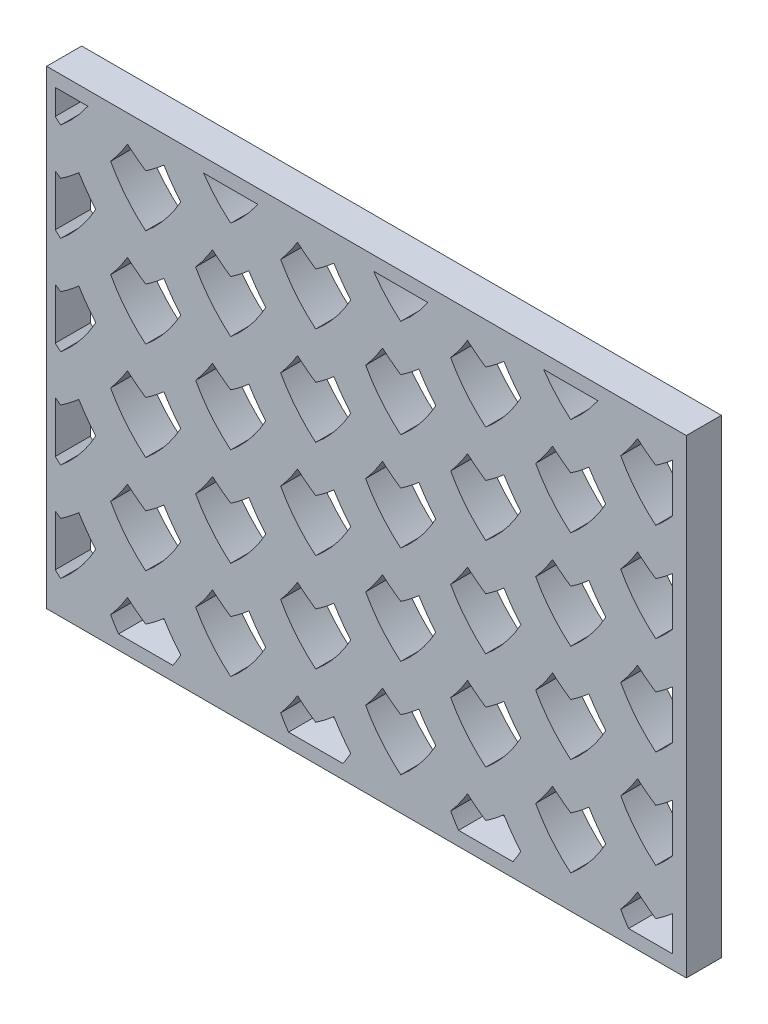
SolidWorks part; units mm, degrees
ref_plane "Front Plane" through (0, 0, 0) normal (0, 0, 1) x (1, 0, 0)
ref_plane "Top Plane" through (0, 0, 0) normal (0, 1, 0) x (1, 0, 0)
ref_plane "Right Plane" through (0, 0, 0) normal (1, 0, 0) x (0, 0, -1)
sketch "Sketch1" plane through (0, 0, 0) normal (0, 0, 1) x (1, 0, 0)
  line L0 (-49.5912, -69.1179) -> (-37.4668, -62.1179) construction
  arc A0 (-49.5912, -69.1179) -> (-54.5912, -63.0266) centre (-35.8066, -52.7051) cw
  arc A1 (-54.5912, -63.0266) -> (-52.1853, -59.6939) centre (-73.3707, -46.9345) ccw
  arc A2 (-49.5912, -61.697) -> (-52.1853, -59.6939) centre (-35.8066, -41.1639) cw
  arc A3 (-49.5912, -61.697) -> (-46.9971, -59.6939) centre (-63.3758, -41.1639) ccw
  arc A4 (-44.5911, -63.0266) -> (-46.9971, -59.6939) centre (-25.8117, -46.9345) cw
  arc A5 (-49.5912, -69.1179) -> (-44.5911, -63.0266) centre (-63.3758, -52.7051) ccw
  arc A6 (-37.4668, -62.1179) -> (-42.4669, -56.0266) centre (-23.6822, -45.7051) cw
  arc A7 (-42.4669, -56.0266) -> (-40.061, -52.6939) centre (-61.2463, -39.9345) ccw
  arc A8 (-37.4668, -54.697) -> (-40.061, -52.6939) centre (-23.6822, -34.1639) cw
  arc A9 (-37.4668, -54.697) -> (-34.8727, -52.6939) centre (-51.2514, -34.1639) ccw
  arc A10 (-32.4668, -56.0266) -> (-34.8727, -52.6939) centre (-13.6873, -39.9345) cw
  arc A11 (-37.4668, -62.1179) -> (-32.4668, -56.0266) centre (-51.2514, -45.7051) ccw
  arc A12 (-25.3425, -55.1179) -> (-30.3425, -49.0266) centre (-11.5579, -38.7051) cw
  arc A13 (-30.3425, -49.0266) -> (-27.9366, -45.6939) centre (-49.122, -32.9345) ccw
  arc A14 (-25.3425, -47.697) -> (-27.9366, -45.6939) centre (-11.5579, -27.1639) cw
  arc A15 (-25.3425, -47.697) -> (-22.7483, -45.6939) centre (-39.1271, -27.1639) ccw
  arc A16 (-20.3424, -49.0266) -> (-22.7483, -45.6939) centre (-1.563, -32.9345) cw
  arc A17 (-25.3425, -55.1179) -> (-20.3424, -49.0266) centre (-39.1271, -38.7051) ccw
  arc A18 (-13.2181, -48.1179) -> (-18.2182, -42.0266) centre (0.5665, -31.7051) cw
  arc A19 (-18.2182, -42.0266) -> (-15.8123, -38.6939) centre (-36.9976, -25.9345) ccw
  arc A20 (-13.2181, -40.697) -> (-15.8123, -38.6939) centre (0.5665, -20.1639) cw
  arc A21 (-13.2181, -40.697) -> (-10.624, -38.6939) centre (-27.0027, -20.1639) ccw
  arc A22 (-8.2181, -42.0266) -> (-10.624, -38.6939) centre (10.5614, -25.9345) cw
  arc A23 (-13.2181, -48.1179) -> (-8.2181, -42.0266) centre (-27.0027, -31.7051) ccw
  arc A24 (-1.0938, -41.1179) -> (-6.0938, -35.0266) centre (12.6908, -24.7051) cw
  arc A25 (-6.0938, -35.0266) -> (-3.6879, -31.6939) centre (-24.8733, -18.9345) ccw
  arc A26 (-1.0938, -33.697) -> (-3.6879, -31.6939) centre (12.6908, -13.1639) cw
  arc A27 (-1.0938, -33.697) -> (1.5004, -31.6939) centre (-14.8783, -13.1639) ccw
  arc A28 (3.9063, -35.0266) -> (1.5004, -31.6939) centre (22.6857, -18.9345) cw
  arc A29 (-1.0938, -41.1179) -> (3.9063, -35.0266) centre (-14.8783, -24.7051) ccw
  arc A30 (11.0306, -34.1179) -> (6.0305, -28.0266) centre (24.8152, -17.7051) cw
  arc A31 (6.0305, -28.0266) -> (8.4365, -24.6939) centre (-12.7489, -11.9345) ccw
  arc A32 (11.0306, -26.697) -> (8.4365, -24.6939) centre (24.8152, -6.1639) cw
  arc A33 (11.0306, -26.697) -> (13.6247, -24.6939) centre (-2.754, -6.1639) ccw
  arc A34 (16.0306, -28.0266) -> (13.6247, -24.6939) centre (34.8101, -11.9345) cw
  arc A35 (11.0306, -34.1179) -> (16.0306, -28.0266) centre (-2.754, -17.7051) ccw
  arc A36 (23.1549, -27.1179) -> (18.1549, -21.0266) centre (36.9395, -10.7051) cw
  arc A37 (18.1549, -21.0266) -> (20.5608, -17.6939) centre (-0.6246, -4.9345) ccw
  arc A38 (23.1549, -19.697) -> (20.5608, -17.6939) centre (36.9395, 0.8361) cw
  arc A39 (23.1549, -19.697) -> (25.7491, -17.6939) centre (9.3704, 0.8361) ccw
  arc A40 (28.155, -21.0266) -> (25.7491, -17.6939) centre (46.9344, -4.9345) cw
  arc A41 (23.1549, -27.1179) -> (28.155, -21.0266) centre (9.3704, -10.7051) ccw
  arc A42 (35.2793, -20.1179) -> (30.2792, -14.0266) centre (49.0639, -3.7051) cw
  arc A43 (30.2792, -14.0266) -> (32.6852, -10.6939) centre (11.4998, 2.0655) ccw
  arc A44 (35.2793, -12.697) -> (32.6852, -10.6939) centre (49.0639, 7.8361) cw
  arc A45 (35.2793, -12.697) -> (37.8734, -10.6939) centre (21.4947, 7.8361) ccw
  arc A46 (40.2794, -14.0266) -> (37.8734, -10.6939) centre (59.0588, 2.0655) cw
  arc A47 (35.2793, -20.1179) -> (40.2794, -14.0266) centre (21.4947, -3.7051) ccw
  arc A48 (47.4037, -13.1179) -> (42.4036, -7.0266) centre (61.1882, 3.2949) cw
  arc A49 (42.4036, -7.0266) -> (44.8095, -3.6939) centre (23.6242, 9.0655) ccw
  arc A50 (47.4037, -5.697) -> (44.8095, -3.6939) centre (61.1882, 14.8361) cw
  arc A51 (47.4037, -5.697) -> (49.9978, -3.6939) centre (33.6191, 14.8361) ccw
  arc A52 (52.4037, -7.0266) -> (49.9978, -3.6939) centre (71.1832, 9.0655) cw
  arc A53 (47.4037, -13.1179) -> (52.4037, -7.0266) centre (33.6191, 3.2949) ccw
  arc A54 (59.528, -6.1179) -> (54.528, -0.0266) centre (73.3126, 10.2949) cw
  arc A55 (54.528, -0.0266) -> (56.9339, 3.3061) centre (35.7485, 16.0655) ccw
  arc A56 (59.528, 1.303) -> (56.9339, 3.3061) centre (73.3126, 21.8361) cw
  arc A57 (59.528, 1.303) -> (62.1221, 3.3061) centre (45.7434, 21.8361) ccw
  arc A58 (64.5281, -0.0266) -> (62.1221, 3.3061) centre (83.3075, 16.0655) cw
  arc A59 (59.528, -6.1179) -> (64.5281, -0.0266) centre (45.7434, 10.2949) ccw
  arc A60 (-37.4668, -48.1179) -> (-42.4669, -42.0266) centre (-23.6822, -31.7051) cw
  arc A61 (-42.4669, -42.0266) -> (-40.061, -38.6939) centre (-61.2463, -25.9345) ccw
  arc A62 (-37.4668, -40.697) -> (-40.061, -38.6939) centre (-23.6822, -20.1639) cw
  arc A63 (-37.4668, -40.697) -> (-34.8727, -38.6939) centre (-51.2514, -20.1639) ccw
  arc A64 (-32.4668, -42.0266) -> (-34.8727, -38.6939) centre (-13.6873, -25.9345) cw
  arc A65 (-37.4668, -48.1179) -> (-32.4668, -42.0266) centre (-51.2514, -31.7051) ccw
  arc A66 (-25.3425, -41.1179) -> (-30.3425, -35.0266) centre (-11.5579, -24.7051) cw
  arc A67 (-30.3425, -35.0266) -> (-27.9366, -31.6939) centre (-49.122, -18.9345) ccw
  arc A68 (-25.3425, -33.697) -> (-27.9366, -31.6939) centre (-11.5579, -13.1639) cw
  arc A69 (-25.3425, -33.697) -> (-22.7483, -31.6939) centre (-39.1271, -13.1639) ccw
  arc A70 (-20.3424, -35.0266) -> (-22.7483, -31.6939) centre (-1.563, -18.9345) cw
  arc A71 (-25.3425, -41.1179) -> (-20.3424, -35.0266) centre (-39.1271, -24.7051) ccw
  arc A72 (-13.2181, -34.1179) -> (-18.2182, -28.0266) centre (0.5665, -17.7051) cw
  arc A73 (-18.2182, -28.0266) -> (-15.8123, -24.6939) centre (-36.9976, -11.9345) ccw
  arc A74 (-13.2181, -26.697) -> (-15.8123, -24.6939) centre (0.5665, -6.1639) cw
  arc A75 (-13.2181, -26.697) -> (-10.624, -24.6939) centre (-27.0027, -6.1639) ccw
  arc A76 (-8.2181, -28.0266) -> (-10.624, -24.6939) centre (10.5614, -11.9345) cw
  arc A77 (-13.2181, -34.1179) -> (-8.2181, -28.0266) centre (-27.0027, -17.7051) ccw
  arc A78 (-1.0938, -27.1179) -> (-6.0938, -21.0266) centre (12.6908, -10.7051) cw
  arc A79 (-6.0938, -21.0266) -> (-3.6879, -17.6939) centre (-24.8733, -4.9345) ccw
  arc A80 (-1.0938, -19.697) -> (-3.6879, -17.6939) centre (12.6908, 0.8361) cw
  arc A81 (-1.0938, -19.697) -> (1.5004, -17.6939) centre (-14.8783, 0.8361) ccw
  arc A82 (3.9063, -21.0266) -> (1.5004, -17.6939) centre (22.6857, -4.9345) cw
  arc A83 (-1.0938, -27.1179) -> (3.9063, -21.0266) centre (-14.8783, -10.7051) ccw
  arc A84 (11.0306, -20.1179) -> (6.0305, -14.0266) centre (24.8152, -3.7051) cw
  arc A85 (6.0305, -14.0266) -> (8.4365, -10.6939) centre (-12.7489, 2.0655) ccw
  arc A86 (11.0306, -12.697) -> (8.4365, -10.6939) centre (24.8152, 7.8361) cw
  arc A87 (11.0306, -12.697) -> (13.6247, -10.6939) centre (-2.754, 7.8361) ccw
  arc A88 (16.0306, -14.0266) -> (13.6247, -10.6939) centre (34.8101, 2.0655) cw
  arc A89 (11.0306, -20.1179) -> (16.0306, -14.0266) centre (-2.754, -3.7051) ccw
  arc A90 (23.1549, -13.1179) -> (18.1549, -7.0266) centre (36.9395, 3.2949) cw
  arc A91 (18.1549, -7.0266) -> (20.5608, -3.6939) centre (-0.6246, 9.0655) ccw
  arc A92 (23.1549, -5.697) -> (20.5608, -3.6939) centre (36.9395, 14.8361) cw
  arc A93 (23.1549, -5.697) -> (25.7491, -3.6939) centre (9.3704, 14.8361) ccw
  arc A94 (28.155, -7.0266) -> (25.7491, -3.6939) centre (46.9344, 9.0655) cw
  arc A95 (23.1549, -13.1179) -> (28.155, -7.0266) centre (9.3704, 3.2949) ccw
  arc A96 (35.2793, -6.1179) -> (30.2792, -0.0266) centre (49.0639, 10.2949) cw
  arc A97 (30.2792, -0.0266) -> (32.6852, 3.3061) centre (11.4998, 16.0655) ccw
  arc A98 (35.2793, 1.303) -> (32.6852, 3.3061) centre (49.0639, 21.8361) cw
  arc A99 (35.2793, 1.303) -> (37.8734, 3.3061) centre (21.4947, 21.8361) ccw
  arc A100 (40.2794, -0.0266) -> (37.8734, 3.3061) centre (59.0588, 16.0655) cw
  arc A101 (35.2793, -6.1179) -> (40.2794, -0.0266) centre (21.4947, 10.2949) ccw
  arc A102 (47.4037, 0.8821) -> (42.4036, 6.9734) centre (61.1882, 17.2949) cw
  arc A103 (42.4036, 6.9734) -> (44.8095, 10.3061) centre (23.6242, 23.0655) ccw
  arc A104 (47.4037, 8.303) -> (44.8095, 10.3061) centre (61.1882, 28.8361) cw
  arc A105 (47.4037, 8.303) -> (49.9978, 10.3061) centre (33.6191, 28.8361) ccw
  arc A106 (52.4037, 6.9734) -> (49.9978, 10.3061) centre (71.1832, 23.0655) cw
  arc A107 (47.4037, 0.8821) -> (52.4037, 6.9734) centre (33.6191, 17.2949) ccw
  arc A108 (59.528, 7.8821) -> (54.528, 13.9734) centre (73.3126, 24.2949) cw
  arc A109 (54.528, 13.9734) -> (56.9339, 17.3061) centre (35.7485, 30.0655) ccw
  arc A110 (59.528, 15.303) -> (56.9339, 17.3061) centre (73.3126, 35.8361) cw
  arc A111 (59.528, 15.303) -> (62.1221, 17.3061) centre (45.7434, 35.8361) ccw
  arc A112 (64.5281, 13.9734) -> (62.1221, 17.3061) centre (83.3075, 30.0655) cw
  arc A113 (59.528, 7.8821) -> (64.5281, 13.9734) centre (45.7434, 24.2949) ccw
  arc A114 (-37.4668, -34.1179) -> (-42.4669, -28.0266) centre (-23.6822, -17.7051) cw
  arc A115 (-42.4669, -28.0266) -> (-40.061, -24.6939) centre (-61.2463, -11.9345) ccw
  arc A116 (-37.4668, -26.697) -> (-40.061, -24.6939) centre (-23.6822, -6.1639) cw
  arc A117 (-37.4668, -26.697) -> (-34.8727, -24.6939) centre (-51.2514, -6.1639) ccw
  arc A118 (-32.4668, -28.0266) -> (-34.8727, -24.6939) centre (-13.6873, -11.9345) cw
  arc A119 (-37.4668, -34.1179) -> (-32.4668, -28.0266) centre (-51.2514, -17.7051) ccw
  arc A120 (-25.3425, -27.1179) -> (-30.3425, -21.0266) centre (-11.5579, -10.7051) cw
  arc A121 (-30.3425, -21.0266) -> (-27.9366, -17.6939) centre (-49.122, -4.9345) ccw
  arc A122 (-25.3425, -19.697) -> (-27.9366, -17.6939) centre (-11.5579, 0.8361) cw
  arc A123 (-25.3425, -19.697) -> (-22.7483, -17.6939) centre (-39.1271, 0.8361) ccw
  arc A124 (-20.3424, -21.0266) -> (-22.7483, -17.6939) centre (-1.563, -4.9345) cw
  arc A125 (-25.3425, -27.1179) -> (-20.3424, -21.0266) centre (-39.1271, -10.7051) ccw
  arc A126 (-13.2181, -20.1179) -> (-18.2182, -14.0266) centre (0.5665, -3.7051) cw
  arc A127 (-18.2182, -14.0266) -> (-15.8123, -10.6939) centre (-36.9976, 2.0655) ccw
  arc A128 (-13.2181, -12.697) -> (-15.8123, -10.6939) centre (0.5665, 7.8361) cw
  arc A129 (-13.2181, -12.697) -> (-10.624, -10.6939) centre (-27.0027, 7.8361) ccw
  arc A130 (-8.2181, -14.0266) -> (-10.624, -10.6939) centre (10.5614, 2.0655) cw
  arc A131 (-13.2181, -20.1179) -> (-8.2181, -14.0266) centre (-27.0027, -3.7051) ccw
  arc A132 (-1.0938, -13.1179) -> (-6.0938, -7.0266) centre (12.6908, 3.2949) cw
  arc A133 (-6.0938, -7.0266) -> (-3.6879, -3.6939) centre (-24.8733, 9.0655) ccw
  arc A134 (-1.0938, -5.697) -> (-3.6879, -3.6939) centre (12.6908, 14.8361) cw
  arc A135 (-1.0938, -5.697) -> (1.5004, -3.6939) centre (-14.8783, 14.8361) ccw
  arc A136 (3.9063, -7.0266) -> (1.5004, -3.6939) centre (22.6857, 9.0655) cw
  arc A137 (-1.0938, -13.1179) -> (3.9063, -7.0266) centre (-14.8783, 3.2949) ccw
  arc A138 (11.0306, -6.1179) -> (6.0305, -0.0266) centre (24.8152, 10.2949) cw
  arc A139 (6.0305, -0.0266) -> (8.4365, 3.3061) centre (-12.7489, 16.0655) ccw
  arc A140 (11.0306, 1.303) -> (8.4365, 3.3061) centre (24.8152, 21.8361) cw
  arc A141 (11.0306, 1.303) -> (13.6247, 3.3061) centre (-2.754, 21.8361) ccw
  arc A142 (16.0306, -0.0266) -> (13.6247, 3.3061) centre (34.8101, 16.0655) cw
  arc A143 (11.0306, -6.1179) -> (16.0306, -0.0266) centre (-2.754, 10.2949) ccw
  arc A144 (23.1549, 0.8821) -> (18.1549, 6.9734) centre (36.9395, 17.2949) cw
  arc A145 (18.1549, 6.9734) -> (20.5608, 10.3061) centre (-0.6246, 23.0655) ccw
  arc A146 (23.1549, 8.303) -> (20.5608, 10.3061) centre (36.9395, 28.8361) cw
  arc A147 (23.1549, 8.303) -> (25.7491, 10.3061) centre (9.3704, 28.8361) ccw
  arc A148 (28.155, 6.9734) -> (25.7491, 10.3061) centre (46.9344, 23.0655) cw
  arc A149 (23.1549, 0.8821) -> (28.155, 6.9734) centre (9.3704, 17.2949) ccw
  arc A150 (35.2793, 7.8821) -> (30.2792, 13.9734) centre (49.0639, 24.2949) cw
  arc A151 (30.2792, 13.9734) -> (32.6852, 17.3061) centre (11.4998, 30.0655) ccw
  arc A152 (35.2793, 15.303) -> (32.6852, 17.3061) centre (49.0639, 35.8361) cw
  arc A153 (35.2793, 15.303) -> (37.8734, 17.3061) centre (21.4947, 35.8361) ccw
  arc A154 (40.2794, 13.9734) -> (37.8734, 17.3061) centre (59.0588, 30.0655) cw
  arc A155 (35.2793, 7.8821) -> (40.2794, 13.9734) centre (21.4947, 24.2949) ccw
  arc A156 (47.4037, 14.8821) -> (42.4036, 20.9734) centre (61.1882, 31.2949) cw
  arc A157 (42.4036, 20.9734) -> (44.8095, 24.3061) centre (23.6242, 37.0655) ccw
  arc A158 (47.4037, 22.303) -> (44.8095, 24.3061) centre (61.1882, 42.8361) cw
  arc A159 (47.4037, 22.303) -> (49.9978, 24.3061) centre (33.6191, 42.8361) ccw
  arc A160 (52.4037, 20.9734) -> (49.9978, 24.3061) centre (71.1832, 37.0655) cw
  arc A161 (47.4037, 14.8821) -> (52.4037, 20.9734) centre (33.6191, 31.2949) ccw
  arc A162 (59.528, 21.8821) -> (54.528, 27.9734) centre (73.3126, 38.2949) cw
  arc A163 (54.528, 27.9734) -> (56.9339, 31.3061) centre (35.7485, 44.0655) ccw
  arc A164 (59.528, 29.303) -> (56.9339, 31.3061) centre (73.3126, 49.8361) cw
  arc A165 (59.528, 29.303) -> (62.1221, 31.3061) centre (45.7434, 49.8361) ccw
  arc A166 (64.5281, 27.9734) -> (62.1221, 31.3061) centre (83.3075, 44.0655) cw
  arc A167 (59.528, 21.8821) -> (64.5281, 27.9734) centre (45.7434, 38.2949) ccw
  arc A168 (-37.4668, -20.1179) -> (-42.4669, -14.0266) centre (-23.6822, -3.7051) cw
  arc A169 (-42.4669, -14.0266) -> (-40.061, -10.6939) centre (-61.2463, 2.0655) ccw
  arc A170 (-37.4668, -12.697) -> (-40.061, -10.6939) centre (-23.6822, 7.8361) cw
  arc A171 (-37.4668, -12.697) -> (-34.8727, -10.6939) centre (-51.2514, 7.8361) ccw
  arc A172 (-32.4668, -14.0266) -> (-34.8727, -10.6939) centre (-13.6873, 2.0655) cw
  arc A173 (-37.4668, -20.1179) -> (-32.4668, -14.0266) centre (-51.2514, -3.7051) ccw
  arc A174 (-25.3425, -13.1179) -> (-30.3425, -7.0266) centre (-11.5579, 3.2949) cw
  arc A175 (-30.3425, -7.0266) -> (-27.9366, -3.6939) centre (-49.122, 9.0655) ccw
  arc A176 (-25.3425, -5.697) -> (-27.9366, -3.6939) centre (-11.5579, 14.8361) cw
  arc A177 (-25.3425, -5.697) -> (-22.7483, -3.6939) centre (-39.1271, 14.8361) ccw
  arc A178 (-20.3424, -7.0266) -> (-22.7483, -3.6939) centre (-1.563, 9.0655) cw
  arc A179 (-25.3425, -13.1179) -> (-20.3424, -7.0266) centre (-39.1271, 3.2949) ccw
  arc A180 (-13.2181, -6.1179) -> (-18.2182, -0.0266) centre (0.5665, 10.2949) cw
  arc A181 (-18.2182, -0.0266) -> (-15.8123, 3.3061) centre (-36.9976, 16.0655) ccw
  arc A182 (-13.2181, 1.303) -> (-15.8123, 3.3061) centre (0.5665, 21.8361) cw
  arc A183 (-13.2181, 1.303) -> (-10.624, 3.3061) centre (-27.0027, 21.8361) ccw
  arc A184 (-8.2181, -0.0266) -> (-10.624, 3.3061) centre (10.5614, 16.0655) cw
  arc A185 (-13.2181, -6.1179) -> (-8.2181, -0.0266) centre (-27.0027, 10.2949) ccw
  arc A186 (-1.0938, 0.8821) -> (-6.0938, 6.9734) centre (12.6908, 17.2949) cw
  arc A187 (-6.0938, 6.9734) -> (-3.6879, 10.3061) centre (-24.8733, 23.0655) ccw
  arc A188 (-1.0938, 8.303) -> (-3.6879, 10.3061) centre (12.6908, 28.8361) cw
  arc A189 (-1.0938, 8.303) -> (1.5004, 10.3061) centre (-14.8783, 28.8361) ccw
  arc A190 (3.9063, 6.9734) -> (1.5004, 10.3061) centre (22.6857, 23.0655) cw
  arc A191 (-1.0938, 0.8821) -> (3.9063, 6.9734) centre (-14.8783, 17.2949) ccw
  arc A192 (11.0306, 7.8821) -> (6.0305, 13.9734) centre (24.8152, 24.2949) cw
  arc A193 (6.0305, 13.9734) -> (8.4365, 17.3061) centre (-12.7489, 30.0655) ccw
  arc A194 (11.0306, 15.303) -> (8.4365, 17.3061) centre (24.8152, 35.8361) cw
  arc A195 (11.0306, 15.303) -> (13.6247, 17.3061) centre (-2.754, 35.8361) ccw
  arc A196 (16.0306, 13.9734) -> (13.6247, 17.3061) centre (34.8101, 30.0655) cw
  arc A197 (11.0306, 7.8821) -> (16.0306, 13.9734) centre (-2.754, 24.2949) ccw
  arc A198 (23.1549, 14.8821) -> (18.1549, 20.9734) centre (36.9395, 31.2949) cw
  arc A199 (18.1549, 20.9734) -> (20.5608, 24.3061) centre (-0.6246, 37.0655) ccw
  arc A200 (23.1549, 22.303) -> (20.5608, 24.3061) centre (36.9395, 42.8361) cw
  arc A201 (23.1549, 22.303) -> (25.7491, 24.3061) centre (9.3704, 42.8361) ccw
  arc A202 (28.155, 20.9734) -> (25.7491, 24.3061) centre (46.9344, 37.0655) cw
  arc A203 (23.1549, 14.8821) -> (28.155, 20.9734) centre (9.3704, 31.2949) ccw
  arc A204 (35.2793, 21.8821) -> (30.2792, 27.9734) centre (49.0639, 38.2949) cw
  arc A205 (30.2792, 27.9734) -> (32.6852, 31.3061) centre (11.4998, 44.0655) ccw
  arc A206 (35.2793, 29.303) -> (32.6852, 31.3061) centre (49.0639, 49.8361) cw
  arc A207 (35.2793, 29.303) -> (37.8734, 31.3061) centre (21.4947, 49.8361) ccw
  arc A208 (40.2794, 27.9734) -> (37.8734, 31.3061) centre (59.0588, 44.0655) cw
  arc A209 (35.2793, 21.8821) -> (40.2794, 27.9734) centre (21.4947, 38.2949) ccw
  arc A210 (47.4037, 28.8821) -> (42.4036, 34.9734) centre (61.1882, 45.2949) cw
  arc A211 (42.4036, 34.9734) -> (44.8095, 38.3061) centre (23.6242, 51.0655) ccw
  arc A212 (47.4037, 36.303) -> (44.8095, 38.3061) centre (61.1882, 56.8361) cw
  arc A213 (47.4037, 36.303) -> (49.9978, 38.3061) centre (33.6191, 56.8361) ccw
  arc A214 (52.4037, 34.9734) -> (49.9978, 38.3061) centre (71.1832, 51.0655) cw
  arc A215 (47.4037, 28.8821) -> (52.4037, 34.9734) centre (33.6191, 45.2949) ccw
  arc A216 (59.528, 35.8821) -> (54.528, 41.9734) centre (73.3126, 52.2949) cw
  arc A217 (54.528, 41.9734) -> (56.9339, 45.3061) centre (35.7485, 58.0655) ccw
  arc A218 (59.528, 43.303) -> (56.9339, 45.3061) centre (73.3126, 63.8361) cw
  arc A219 (59.528, 43.303) -> (62.1221, 45.3061) centre (45.7434, 63.8361) ccw
  arc A220 (64.5281, 41.9734) -> (62.1221, 45.3061) centre (83.3075, 58.0655) cw
  arc A221 (59.528, 35.8821) -> (64.5281, 41.9734) centre (45.7434, 52.2949) ccw
  arc A222 (-37.4668, -6.1179) -> (-42.4669, -0.0266) centre (-23.6822, 10.2949) cw
  arc A223 (-42.4669, -0.0266) -> (-40.061, 3.3061) centre (-61.2463, 16.0655) ccw
  arc A224 (-37.4668, 1.303) -> (-40.061, 3.3061) centre (-23.6822, 21.8361) cw
  arc A225 (-37.4668, 1.303) -> (-34.8727, 3.3061) centre (-51.2514, 21.8361) ccw
  arc A226 (-32.4668, -0.0266) -> (-34.8727, 3.3061) centre (-13.6873, 16.0655) cw
  arc A227 (-37.4668, -6.1179) -> (-32.4668, -0.0266) centre (-51.2514, 10.2949) ccw
  arc A228 (-25.3425, 0.8821) -> (-30.3425, 6.9734) centre (-11.5579, 17.2949) cw
  arc A229 (-30.3425, 6.9734) -> (-27.9366, 10.3061) centre (-49.122, 23.0655) ccw
  arc A230 (-25.3425, 8.303) -> (-27.9366, 10.3061) centre (-11.5579, 28.8361) cw
  arc A231 (-25.3425, 8.303) -> (-22.7483, 10.3061) centre (-39.1271, 28.8361) ccw
  arc A232 (-20.3424, 6.9734) -> (-22.7483, 10.3061) centre (-1.563, 23.0655) cw
  arc A233 (-25.3425, 0.8821) -> (-20.3424, 6.9734) centre (-39.1271, 17.2949) ccw
  arc A234 (-13.2181, 7.8821) -> (-18.2182, 13.9734) centre (0.5665, 24.2949) cw
  arc A235 (-18.2182, 13.9734) -> (-15.8123, 17.3061) centre (-36.9976, 30.0655) ccw
  arc A236 (-13.2181, 15.303) -> (-15.8123, 17.3061) centre (0.5665, 35.8361) cw
  arc A237 (-13.2181, 15.303) -> (-10.624, 17.3061) centre (-27.0027, 35.8361) ccw
  arc A238 (-8.2181, 13.9734) -> (-10.624, 17.3061) centre (10.5614, 30.0655) cw
  arc A239 (-13.2181, 7.8821) -> (-8.2181, 13.9734) centre (-27.0027, 24.2949) ccw
  arc A240 (-1.0938, 14.8821) -> (-6.0938, 20.9734) centre (12.6908, 31.2949) cw
  arc A241 (-6.0938, 20.9734) -> (-3.6879, 24.3061) centre (-24.8733, 37.0655) ccw
  arc A242 (-1.0938, 22.303) -> (-3.6879, 24.3061) centre (12.6908, 42.8361) cw
  arc A243 (-1.0938, 22.303) -> (1.5004, 24.3061) centre (-14.8783, 42.8361) ccw
  arc A244 (3.9063, 20.9734) -> (1.5004, 24.3061) centre (22.6857, 37.0655) cw
  arc A245 (-1.0938, 14.8821) -> (3.9063, 20.9734) centre (-14.8783, 31.2949) ccw
  arc A246 (11.0306, 21.8821) -> (6.0305, 27.9734) centre (24.8152, 38.2949) cw
  arc A247 (6.0305, 27.9734) -> (8.4365, 31.3061) centre (-12.7489, 44.0655) ccw
  arc A248 (11.0306, 29.303) -> (8.4365, 31.3061) centre (24.8152, 49.8361) cw
  arc A249 (11.0306, 29.303) -> (13.6247, 31.3061) centre (-2.754, 49.8361) ccw
  arc A250 (16.0306, 27.9734) -> (13.6247, 31.3061) centre (34.8101, 44.0655) cw
  arc A251 (11.0306, 21.8821) -> (16.0306, 27.9734) centre (-2.754, 38.2949) ccw
  arc A252 (23.1549, 28.8821) -> (18.1549, 34.9734) centre (36.9395, 45.2949) cw
  arc A253 (18.1549, 34.9734) -> (20.5608, 38.3061) centre (-0.6246, 51.0655) ccw
  arc A254 (23.1549, 36.303) -> (20.5608, 38.3061) centre (36.9395, 56.8361) cw
  arc A255 (23.1549, 36.303) -> (25.7491, 38.3061) centre (9.3704, 56.8361) ccw
  arc A256 (28.155, 34.9734) -> (25.7491, 38.3061) centre (46.9344, 51.0655) cw
  arc A257 (23.1549, 28.8821) -> (28.155, 34.9734) centre (9.3704, 45.2949) ccw
  arc A258 (35.2793, 35.8821) -> (30.2792, 41.9734) centre (49.0639, 52.2949) cw
  arc A259 (30.2792, 41.9734) -> (32.6852, 45.3061) centre (11.4998, 58.0655) ccw
  arc A260 (35.2793, 43.303) -> (32.6852, 45.3061) centre (49.0639, 63.8361) cw
  arc A261 (35.2793, 43.303) -> (37.8734, 45.3061) centre (21.4947, 63.8361) ccw
  arc A262 (40.2794, 41.9734) -> (37.8734, 45.3061) centre (59.0588, 58.0655) cw
  arc A263 (35.2793, 35.8821) -> (40.2794, 41.9734) centre (21.4947, 52.2949) ccw
  arc A264 (47.4037, 42.8821) -> (42.4036, 48.9734) centre (61.1882, 59.2949) cw
  arc A265 (42.4036, 48.9734) -> (44.8095, 52.3061) centre (23.6242, 65.0655) ccw
  arc A266 (47.4037, 50.303) -> (44.8095, 52.3061) centre (61.1882, 70.8361) cw
  arc A267 (47.4037, 50.303) -> (49.9978, 52.3061) centre (33.6191, 70.8361) ccw
  arc A268 (52.4037, 48.9734) -> (49.9978, 52.3061) centre (71.1832, 65.0655) cw
  arc A269 (47.4037, 42.8821) -> (52.4037, 48.9734) centre (33.6191, 59.2949) ccw
  arc A270 (59.528, 49.8821) -> (54.528, 55.9734) centre (73.3126, 66.2949) cw
  arc A271 (54.528, 55.9734) -> (56.9339, 59.3061) centre (35.7485, 72.0655) ccw
  arc A272 (59.528, 57.303) -> (56.9339, 59.3061) centre (73.3126, 77.8361) cw
  arc A273 (59.528, 57.303) -> (62.1221, 59.3061) centre (45.7434, 77.8361) ccw
  arc A274 (64.5281, 55.9734) -> (62.1221, 59.3061) centre (83.3075, 72.0655) cw
  arc A275 (59.528, 49.8821) -> (64.5281, 55.9734) centre (45.7434, 66.2949) ccw
  arc A276 (-37.4668, 7.8821) -> (-42.4669, 13.9734) centre (-23.6822, 24.2949) cw
  arc A277 (-42.4669, 13.9734) -> (-40.061, 17.3061) centre (-61.2463, 30.0655) ccw
  arc A278 (-37.4668, 15.303) -> (-40.061, 17.3061) centre (-23.6822, 35.8361) cw
  arc A279 (-37.4668, 15.303) -> (-34.8727, 17.3061) centre (-51.2514, 35.8361) ccw
  arc A280 (-32.4668, 13.9734) -> (-34.8727, 17.3061) centre (-13.6873, 30.0655) cw
  arc A281 (-37.4668, 7.8821) -> (-32.4668, 13.9734) centre (-51.2514, 24.2949) ccw
  arc A282 (-25.3425, 14.8821) -> (-30.3425, 20.9734) centre (-11.5579, 31.2949) cw
  arc A283 (-30.3425, 20.9734) -> (-27.9366, 24.3061) centre (-49.122, 37.0655) ccw
  arc A284 (-25.3425, 22.303) -> (-27.9366, 24.3061) centre (-11.5579, 42.8361) cw
  arc A285 (-25.3425, 22.303) -> (-22.7483, 24.3061) centre (-39.1271, 42.8361) ccw
  arc A286 (-20.3424, 20.9734) -> (-22.7483, 24.3061) centre (-1.563, 37.0655) cw
  arc A287 (-25.3425, 14.8821) -> (-20.3424, 20.9734) centre (-39.1271, 31.2949) ccw
  arc A288 (-13.2181, 21.8821) -> (-18.2182, 27.9734) centre (0.5665, 38.2949) cw
  arc A289 (-18.2182, 27.9734) -> (-15.8123, 31.3061) centre (-36.9976, 44.0655) ccw
  arc A290 (-13.2181, 29.303) -> (-15.8123, 31.3061) centre (0.5665, 49.8361) cw
  arc A291 (-13.2181, 29.303) -> (-10.624, 31.3061) centre (-27.0027, 49.8361) ccw
  arc A292 (-8.2181, 27.9734) -> (-10.624, 31.3061) centre (10.5614, 44.0655) cw
  arc A293 (-13.2181, 21.8821) -> (-8.2181, 27.9734) centre (-27.0027, 38.2949) ccw
  arc A294 (-1.0938, 28.8821) -> (-6.0938, 34.9734) centre (12.6908, 45.2949) cw
  arc A295 (-6.0938, 34.9734) -> (-3.6879, 38.3061) centre (-24.8733, 51.0655) ccw
  arc A296 (-1.0938, 36.303) -> (-3.6879, 38.3061) centre (12.6908, 56.8361) cw
  arc A297 (-1.0938, 36.303) -> (1.5004, 38.3061) centre (-14.8783, 56.8361) ccw
  arc A298 (3.9063, 34.9734) -> (1.5004, 38.3061) centre (22.6857, 51.0655) cw
  arc A299 (-1.0938, 28.8821) -> (3.9063, 34.9734) centre (-14.8783, 45.2949) ccw
  arc A300 (11.0306, 35.8821) -> (6.0305, 41.9734) centre (24.8152, 52.2949) cw
  arc A301 (6.0305, 41.9734) -> (8.4365, 45.3061) centre (-12.7489, 58.0655) ccw
  arc A302 (11.0306, 43.303) -> (8.4365, 45.3061) centre (24.8152, 63.8361) cw
  arc A303 (11.0306, 43.303) -> (13.6247, 45.3061) centre (-2.754, 63.8361) ccw
  arc A304 (16.0306, 41.9734) -> (13.6247, 45.3061) centre (34.8101, 58.0655) cw
  arc A305 (11.0306, 35.8821) -> (16.0306, 41.9734) centre (-2.754, 52.2949) ccw
  arc A306 (23.1549, 42.8821) -> (18.1549, 48.9734) centre (36.9395, 59.2949) cw
  arc A307 (18.1549, 48.9734) -> (20.5608, 52.3061) centre (-0.6246, 65.0655) ccw
  arc A308 (23.1549, 50.303) -> (20.5608, 52.3061) centre (36.9395, 70.8361) cw
  arc A309 (23.1549, 50.303) -> (25.7491, 52.3061) centre (9.3704, 70.8361) ccw
  arc A310 (28.155, 48.9734) -> (25.7491, 52.3061) centre (46.9344, 65.0655) cw
  arc A311 (23.1549, 42.8821) -> (28.155, 48.9734) centre (9.3704, 59.2949) ccw
  arc A312 (35.2793, 49.8821) -> (30.2792, 55.9734) centre (49.0639, 66.2949) cw
  arc A313 (30.2792, 55.9734) -> (32.6852, 59.3061) centre (11.4998, 72.0655) ccw
  arc A314 (35.2793, 57.303) -> (32.6852, 59.3061) centre (49.0639, 77.8361) cw
  arc A315 (35.2793, 57.303) -> (37.8734, 59.3061) centre (21.4947, 77.8361) ccw
  arc A316 (40.2794, 55.9734) -> (37.8734, 59.3061) centre (59.0588, 72.0655) cw
  arc A317 (35.2793, 49.8821) -> (40.2794, 55.9734) centre (21.4947, 66.2949) ccw
  arc A318 (47.4037, 56.8821) -> (42.4036, 62.9734) centre (61.1882, 73.2949) cw
  arc A319 (42.4036, 62.9734) -> (44.8095, 66.3061) centre (23.6242, 79.0655) ccw
  arc A320 (47.4037, 64.303) -> (44.8095, 66.3061) centre (61.1882, 84.8361) cw
  arc A321 (47.4037, 64.303) -> (49.9978, 66.3061) centre (33.6191, 84.8361) ccw
  arc A322 (52.4037, 62.9734) -> (49.9978, 66.3061) centre (71.1832, 79.0655) cw
  arc A323 (47.4037, 56.8821) -> (52.4037, 62.9734) centre (33.6191, 73.2949) ccw
  arc A324 (59.528, 63.8821) -> (54.528, 69.9734) centre (73.3126, 80.2949) cw
  arc A325 (54.528, 69.9734) -> (56.9339, 73.3061) centre (35.7485, 86.0655) ccw
  arc A326 (59.528, 71.303) -> (56.9339, 73.3061) centre (73.3126, 91.8361) cw
  arc A327 (59.528, 71.303) -> (62.1221, 73.3061) centre (45.7434, 91.8361) ccw
  arc A328 (64.5281, 69.9734) -> (62.1221, 73.3061) centre (83.3075, 86.0655) cw
  arc A329 (59.528, 63.8821) -> (64.5281, 69.9734) centre (45.7434, 80.2949) ccw
  arc A330 (-37.4668, 21.8821) -> (-42.4669, 27.9734) centre (-23.6822, 38.2949) cw
  arc A331 (-42.4669, 27.9734) -> (-40.061, 31.3061) centre (-61.2463, 44.0655) ccw
  arc A332 (-37.4668, 29.303) -> (-40.061, 31.3061) centre (-23.6822, 49.8361) cw
  arc A333 (-37.4668, 29.303) -> (-34.8727, 31.3061) centre (-51.2514, 49.8361) ccw
  arc A334 (-32.4668, 27.9734) -> (-34.8727, 31.3061) centre (-13.6873, 44.0655) cw
  arc A335 (-37.4668, 21.8821) -> (-32.4668, 27.9734) centre (-51.2514, 38.2949) ccw
  arc A336 (-25.3425, 28.8821) -> (-30.3425, 34.9734) centre (-11.5579, 45.2949) cw
  arc A337 (-30.3425, 34.9734) -> (-27.9366, 38.3061) centre (-49.122, 51.0655) ccw
  arc A338 (-25.3425, 36.303) -> (-27.9366, 38.3061) centre (-11.5579, 56.8361) cw
  arc A339 (-25.3425, 36.303) -> (-22.7483, 38.3061) centre (-39.1271, 56.8361) ccw
  arc A340 (-20.3424, 34.9734) -> (-22.7483, 38.3061) centre (-1.563, 51.0655) cw
  arc A341 (-25.3425, 28.8821) -> (-20.3424, 34.9734) centre (-39.1271, 45.2949) ccw
  arc A342 (-13.2181, 35.8821) -> (-18.2182, 41.9734) centre (0.5665, 52.2949) cw
  arc A343 (-18.2182, 41.9734) -> (-15.8123, 45.3061) centre (-36.9976, 58.0655) ccw
  arc A344 (-13.2181, 43.303) -> (-15.8123, 45.3061) centre (0.5665, 63.8361) cw
  arc A345 (-13.2181, 43.303) -> (-10.624, 45.3061) centre (-27.0027, 63.8361) ccw
  arc A346 (-8.2181, 41.9734) -> (-10.624, 45.3061) centre (10.5614, 58.0655) cw
  arc A347 (-13.2181, 35.8821) -> (-8.2181, 41.9734) centre (-27.0027, 52.2949) ccw
  arc A348 (-1.0938, 42.8821) -> (-6.0938, 48.9734) centre (12.6908, 59.2949) cw
  arc A349 (-6.0938, 48.9734) -> (-3.6879, 52.3061) centre (-24.8733, 65.0655) ccw
  arc A350 (-1.0938, 50.303) -> (-3.6879, 52.3061) centre (12.6908, 70.8361) cw
  arc A351 (-1.0938, 50.303) -> (1.5004, 52.3061) centre (-14.8783, 70.8361) ccw
  arc A352 (3.9063, 48.9734) -> (1.5004, 52.3061) centre (22.6857, 65.0655) cw
  arc A353 (-1.0938, 42.8821) -> (3.9063, 48.9734) centre (-14.8783, 59.2949) ccw
  arc A354 (11.0306, 49.8821) -> (6.0305, 55.9734) centre (24.8152, 66.2949) cw
  arc A355 (6.0305, 55.9734) -> (8.4365, 59.3061) centre (-12.7489, 72.0655) ccw
  arc A356 (11.0306, 57.303) -> (8.4365, 59.3061) centre (24.8152, 77.8361) cw
  arc A357 (11.0306, 57.303) -> (13.6247, 59.3061) centre (-2.754, 77.8361) ccw
  arc A358 (16.0306, 55.9734) -> (13.6247, 59.3061) centre (34.8101, 72.0655) cw
  arc A359 (11.0306, 49.8821) -> (16.0306, 55.9734) centre (-2.754, 66.2949) ccw
  arc A360 (23.1549, 56.8821) -> (18.1549, 62.9734) centre (36.9395, 73.2949) cw
  arc A361 (18.1549, 62.9734) -> (20.5608, 66.3061) centre (-0.6246, 79.0655) ccw
  arc A362 (23.1549, 64.303) -> (20.5608, 66.3061) centre (36.9395, 84.8361) cw
  arc A363 (23.1549, 64.303) -> (25.7491, 66.3061) centre (9.3704, 84.8361) ccw
  arc A364 (28.155, 62.9734) -> (25.7491, 66.3061) centre (46.9344, 79.0655) cw
  arc A365 (23.1549, 56.8821) -> (28.155, 62.9734) centre (9.3704, 73.2949) ccw
  arc A366 (35.2793, 63.8821) -> (30.2792, 69.9734) centre (49.0639, 80.2949) cw
  arc A367 (30.2792, 69.9734) -> (32.6852, 73.3061) centre (11.4998, 86.0655) ccw
  arc A368 (35.2793, 71.303) -> (32.6852, 73.3061) centre (49.0639, 91.8361) cw
  arc A369 (35.2793, 71.303) -> (37.8734, 73.3061) centre (21.4947, 91.8361) ccw
  arc A370 (40.2794, 69.9734) -> (37.8734, 73.3061) centre (59.0588, 86.0655) cw
  arc A371 (35.2793, 63.8821) -> (40.2794, 69.9734) centre (21.4947, 80.2949) ccw
  arc A372 (47.4037, 70.8821) -> (42.4036, 76.9734) centre (61.1882, 87.2949) cw
  arc A373 (42.4036, 76.9734) -> (44.8095, 80.3061) centre (23.6242, 93.0655) ccw
  arc A374 (47.4037, 78.303) -> (44.8095, 80.3061) centre (61.1882, 98.8361) cw
  arc A375 (47.4037, 78.303) -> (49.9978, 80.3061) centre (33.6191, 98.8361) ccw
  arc A376 (52.4037, 76.9734) -> (49.9978, 80.3061) centre (71.1832, 93.0655) cw
  arc A377 (47.4037, 70.8821) -> (52.4037, 76.9734) centre (33.6191, 87.2949) ccw
  arc A378 (59.528, 77.8821) -> (54.528, 83.9734) centre (73.3126, 94.2949) cw
  arc A379 (54.528, 83.9734) -> (56.9339, 87.3061) centre (35.7485, 100.0655) ccw
  arc A380 (59.528, 85.303) -> (56.9339, 87.3061) centre (73.3126, 105.8361) cw
  arc A381 (59.528, 85.303) -> (62.1221, 87.3061) centre (45.7434, 105.8361) ccw
  arc A382 (64.5281, 83.9734) -> (62.1221, 87.3061) centre (83.3075, 100.0655) cw
  arc A383 (59.528, 77.8821) -> (64.5281, 83.9734) centre (45.7434, 94.2949) ccw
  arc A384 (-37.4668, 35.8821) -> (-42.4669, 41.9734) centre (-23.6822, 52.2949) cw
  arc A385 (-42.4669, 41.9734) -> (-40.061, 45.3061) centre (-61.2463, 58.0655) ccw
  arc A386 (-37.4668, 43.303) -> (-40.061, 45.3061) centre (-23.6822, 63.8361) cw
  arc A387 (-37.4668, 43.303) -> (-34.8727, 45.3061) centre (-51.2514, 63.8361) ccw
  arc A388 (-32.4668, 41.9734) -> (-34.8727, 45.3061) centre (-13.6873, 58.0655) cw
  arc A389 (-37.4668, 35.8821) -> (-32.4668, 41.9734) centre (-51.2514, 52.2949) ccw
  arc A390 (-25.3425, 42.8821) -> (-30.3425, 48.9734) centre (-11.5579, 59.2949) cw
  arc A391 (-30.3425, 48.9734) -> (-27.9366, 52.3061) centre (-49.122, 65.0655) ccw
  arc A392 (-25.3425, 50.303) -> (-27.9366, 52.3061) centre (-11.5579, 70.8361) cw
  arc A393 (-25.3425, 50.303) -> (-22.7483, 52.3061) centre (-39.1271, 70.8361) ccw
  arc A394 (-20.3424, 48.9734) -> (-22.7483, 52.3061) centre (-1.563, 65.0655) cw
  arc A395 (-25.3425, 42.8821) -> (-20.3424, 48.9734) centre (-39.1271, 59.2949) ccw
  arc A396 (-13.2181, 49.8821) -> (-18.2182, 55.9734) centre (0.5665, 66.2949) cw
  arc A397 (-18.2182, 55.9734) -> (-15.8123, 59.3061) centre (-36.9976, 72.0655) ccw
  arc A398 (-13.2181, 57.303) -> (-15.8123, 59.3061) centre (0.5665, 77.8361) cw
  arc A399 (-13.2181, 57.303) -> (-10.624, 59.3061) centre (-27.0027, 77.8361) ccw
  arc A400 (-8.2181, 55.9734) -> (-10.624, 59.3061) centre (10.5614, 72.0655) cw
  arc A401 (-13.2181, 49.8821) -> (-8.2181, 55.9734) centre (-27.0027, 66.2949) ccw
  arc A402 (-1.0938, 56.8821) -> (-6.0938, 62.9734) centre (12.6908, 73.2949) cw
  arc A403 (-6.0938, 62.9734) -> (-3.6879, 66.3061) centre (-24.8733, 79.0655) ccw
  arc A404 (-1.0938, 64.303) -> (-3.6879, 66.3061) centre (12.6908, 84.8361) cw
  arc A405 (-1.0938, 64.303) -> (1.5004, 66.3061) centre (-14.8783, 84.8361) ccw
  arc A406 (3.9063, 62.9734) -> (1.5004, 66.3061) centre (22.6857, 79.0655) cw
  arc A407 (-1.0938, 56.8821) -> (3.9063, 62.9734) centre (-14.8783, 73.2949) ccw
  arc A408 (11.0306, 63.8821) -> (6.0305, 69.9734) centre (24.8152, 80.2949) cw
  arc A409 (6.0305, 69.9734) -> (8.4365, 73.3061) centre (-12.7489, 86.0655) ccw
  arc A410 (11.0306, 71.303) -> (8.4365, 73.3061) centre (24.8152, 91.8361) cw
  arc A411 (11.0306, 71.303) -> (13.6247, 73.3061) centre (-2.754, 91.8361) ccw
  arc A412 (16.0306, 69.9734) -> (13.6247, 73.3061) centre (34.8101, 86.0655) cw
  arc A413 (11.0306, 63.8821) -> (16.0306, 69.9734) centre (-2.754, 80.2949) ccw
  arc A414 (23.1549, 70.8821) -> (18.1549, 76.9734) centre (36.9395, 87.2949) cw
  arc A415 (18.1549, 76.9734) -> (20.5608, 80.3061) centre (-0.6246, 93.0655) ccw
  arc A416 (23.1549, 78.303) -> (20.5608, 80.3061) centre (36.9395, 98.8361) cw
  arc A417 (23.1549, 78.303) -> (25.7491, 80.3061) centre (9.3704, 98.8361) ccw
  arc A418 (28.155, 76.9734) -> (25.7491, 80.3061) centre (46.9344, 93.0655) cw
  arc A419 (23.1549, 70.8821) -> (28.155, 76.9734) centre (9.3704, 87.2949) ccw
  arc A420 (35.2793, 77.8821) -> (30.2792, 83.9734) centre (49.0639, 94.2949) cw
  arc A421 (30.2792, 83.9734) -> (32.6852, 87.3061) centre (11.4998, 100.0655) ccw
  arc A422 (35.2793, 85.303) -> (32.6852, 87.3061) centre (49.0639, 105.8361) cw
  arc A423 (35.2793, 85.303) -> (37.8734, 87.3061) centre (21.4947, 105.8361) ccw
  arc A424 (40.2794, 83.9734) -> (37.8734, 87.3061) centre (59.0588, 100.0655) cw
  arc A425 (35.2793, 77.8821) -> (40.2794, 83.9734) centre (21.4947, 94.2949) ccw
  arc A426 (47.4037, 84.8821) -> (42.4036, 90.9734) centre (61.1882, 101.2949) cw
  arc A427 (42.4036, 90.9734) -> (44.8095, 94.3061) centre (23.6242, 107.0655) ccw
  arc A428 (47.4037, 92.303) -> (44.8095, 94.3061) centre (61.1882, 112.8361) cw
  arc A429 (47.4037, 92.303) -> (49.9978, 94.3061) centre (33.6191, 112.8361) ccw
  arc A430 (52.4037, 90.9734) -> (49.9978, 94.3061) centre (71.1832, 107.0655) cw
  arc A431 (47.4037, 84.8821) -> (52.4037, 90.9734) centre (33.6191, 101.2949) ccw
  arc A432 (59.528, 91.8821) -> (54.528, 97.9734) centre (73.3126, 108.2949) cw
  arc A433 (54.528, 97.9734) -> (56.9339, 101.3061) centre (35.7485, 114.0655) ccw
  arc A434 (59.528, 99.303) -> (56.9339, 101.3061) centre (73.3126, 119.8361) cw
  arc A435 (59.528, 99.303) -> (62.1221, 101.3061) centre (45.7434, 119.8361) ccw
  arc A436 (64.5281, 97.9734) -> (62.1221, 101.3061) centre (83.3075, 114.0655) cw
  arc A437 (59.528, 91.8821) -> (64.5281, 97.9734) centre (45.7434, 108.2949) ccw
  arc A438 (-37.4668, 49.8821) -> (-42.4669, 55.9734) centre (-23.6822, 66.2949) cw
  arc A439 (-42.4669, 55.9734) -> (-40.061, 59.3061) centre (-61.2463, 72.0655) ccw
  arc A440 (-37.4668, 57.303) -> (-40.061, 59.3061) centre (-23.6822, 77.8361) cw
  arc A441 (-37.4668, 57.303) -> (-34.8727, 59.3061) centre (-51.2514, 77.8361) ccw
  arc A442 (-32.4668, 55.9734) -> (-34.8727, 59.3061) centre (-13.6873, 72.0655) cw
  arc A443 (-37.4668, 49.8821) -> (-32.4668, 55.9734) centre (-51.2514, 66.2949) ccw
  arc A444 (-25.3425, 56.8821) -> (-30.3425, 62.9734) centre (-11.5579, 73.2949) cw
  arc A445 (-30.3425, 62.9734) -> (-27.9366, 66.3061) centre (-49.122, 79.0655) ccw
  arc A446 (-25.3425, 64.303) -> (-27.9366, 66.3061) centre (-11.5579, 84.8361) cw
  arc A447 (-25.3425, 64.303) -> (-22.7483, 66.3061) centre (-39.1271, 84.8361) ccw
  arc A448 (-20.3424, 62.9734) -> (-22.7483, 66.3061) centre (-1.563, 79.0655) cw
  arc A449 (-25.3425, 56.8821) -> (-20.3424, 62.9734) centre (-39.1271, 73.2949) ccw
  arc A450 (-13.2181, 63.8821) -> (-18.2182, 69.9734) centre (0.5665, 80.2949) cw
  arc A451 (-18.2182, 69.9734) -> (-15.8123, 73.3061) centre (-36.9976, 86.0655) ccw
  arc A452 (-13.2181, 71.303) -> (-15.8123, 73.3061) centre (0.5665, 91.8361) cw
  arc A453 (-13.2181, 71.303) -> (-10.624, 73.3061) centre (-27.0027, 91.8361) ccw
  arc A454 (-8.2181, 69.9734) -> (-10.624, 73.3061) centre (10.5614, 86.0655) cw
  arc A455 (-13.2181, 63.8821) -> (-8.2181, 69.9734) centre (-27.0027, 80.2949) ccw
  arc A456 (-1.0938, 70.8821) -> (-6.0938, 76.9734) centre (12.6908, 87.2949) cw
  arc A457 (-6.0938, 76.9734) -> (-3.6879, 80.3061) centre (-24.8733, 93.0655) ccw
  arc A458 (-1.0938, 78.303) -> (-3.6879, 80.3061) centre (12.6908, 98.8361) cw
  arc A459 (-1.0938, 78.303) -> (1.5004, 80.3061) centre (-14.8783, 98.8361) ccw
  arc A460 (3.9063, 76.9734) -> (1.5004, 80.3061) centre (22.6857, 93.0655) cw
  arc A461 (-1.0938, 70.8821) -> (3.9063, 76.9734) centre (-14.8783, 87.2949) ccw
  arc A462 (11.0306, 77.8821) -> (6.0305, 83.9734) centre (24.8152, 94.2949) cw
  arc A463 (6.0305, 83.9734) -> (8.4365, 87.3061) centre (-12.7489, 100.0655) ccw
  arc A464 (11.0306, 85.303) -> (8.4365, 87.3061) centre (24.8152, 105.8361) cw
  arc A465 (11.0306, 85.303) -> (13.6247, 87.3061) centre (-2.754, 105.8361) ccw
  arc A466 (16.0306, 83.9734) -> (13.6247, 87.3061) centre (34.8101, 100.0655) cw
  arc A467 (11.0306, 77.8821) -> (16.0306, 83.9734) centre (-2.754, 94.2949) ccw
  arc A468 (23.1549, 84.8821) -> (18.1549, 90.9734) centre (36.9395, 101.2949) cw
  arc A469 (18.1549, 90.9734) -> (20.5608, 94.3061) centre (-0.6246, 107.0655) ccw
  arc A470 (23.1549, 92.303) -> (20.5608, 94.3061) centre (36.9395, 112.8361) cw
  arc A471 (23.1549, 92.303) -> (25.7491, 94.3061) centre (9.3704, 112.8361) ccw
  arc A472 (28.155, 90.9734) -> (25.7491, 94.3061) centre (46.9344, 107.0655) cw
  arc A473 (23.1549, 84.8821) -> (28.155, 90.9734) centre (9.3704, 101.2949) ccw
  arc A474 (35.2793, 91.8821) -> (30.2792, 97.9734) centre (49.0639, 108.2949) cw
  arc A475 (30.2792, 97.9734) -> (32.6852, 101.3061) centre (11.4998, 114.0655) ccw
  arc A476 (35.2793, 99.303) -> (32.6852, 101.3061) centre (49.0639, 119.8361) cw
  arc A477 (35.2793, 99.303) -> (37.8734, 101.3061) centre (21.4947, 119.8361) ccw
  arc A478 (40.2794, 97.9734) -> (37.8734, 101.3061) centre (59.0588, 114.0655) cw
  arc A479 (35.2793, 91.8821) -> (40.2794, 97.9734) centre (21.4947, 108.2949) ccw
  arc A480 (47.4037, 98.8821) -> (42.4036, 104.9734) centre (61.1882, 115.2949) cw
  arc A481 (42.4036, 104.9734) -> (44.8095, 108.3061) centre (23.6242, 121.0655) ccw
  arc A482 (47.4037, 106.303) -> (44.8095, 108.3061) centre (61.1882, 126.8361) cw
  arc A483 (47.4037, 106.303) -> (49.9978, 108.3061) centre (33.6191, 126.8361) ccw
  arc A484 (52.4037, 104.9734) -> (49.9978, 108.3061) centre (71.1832, 121.0655) cw
  arc A485 (47.4037, 98.8821) -> (52.4037, 104.9734) centre (33.6191, 115.2949) ccw
  arc A486 (59.528, 105.8821) -> (54.528, 111.9734) centre (73.3126, 122.2949) cw
  arc A487 (54.528, 111.9734) -> (56.9339, 115.3061) centre (35.7485, 128.0655) ccw
  arc A488 (59.528, 113.303) -> (56.9339, 115.3061) centre (73.3126, 133.8361) cw
  arc A489 (59.528, 113.303) -> (62.1221, 115.3061) centre (45.7434, 133.8361) ccw
  arc A490 (64.5281, 111.9734) -> (62.1221, 115.3061) centre (83.3075, 128.0655) cw
  arc A491 (59.528, 105.8821) -> (64.5281, 111.9734) centre (45.7434, 122.2949) ccw
  arc A492 (-37.4668, 63.8821) -> (-42.4669, 69.9734) centre (-23.6822, 80.2949) cw
  arc A493 (-42.4669, 69.9734) -> (-40.061, 73.3061) centre (-61.2463, 86.0655) ccw
  arc A494 (-37.4668, 71.303) -> (-40.061, 73.3061) centre (-23.6822, 91.8361) cw
  arc A495 (-37.4668, 71.303) -> (-34.8727, 73.3061) centre (-51.2514, 91.8361) ccw
  arc A496 (-32.4668, 69.9734) -> (-34.8727, 73.3061) centre (-13.6873, 86.0655) cw
  arc A497 (-37.4668, 63.8821) -> (-32.4668, 69.9734) centre (-51.2514, 80.2949) ccw
  arc A498 (-25.3425, 70.8821) -> (-30.3425, 76.9734) centre (-11.5579, 87.2949) cw
  arc A499 (-30.3425, 76.9734) -> (-27.9366, 80.3061) centre (-49.122, 93.0655) ccw
  arc A500 (-25.3425, 78.303) -> (-27.9366, 80.3061) centre (-11.5579, 98.8361) cw
  arc A501 (-25.3425, 78.303) -> (-22.7483, 80.3061) centre (-39.1271, 98.8361) ccw
  arc A502 (-20.3424, 76.9734) -> (-22.7483, 80.3061) centre (-1.563, 93.0655) cw
  arc A503 (-25.3425, 70.8821) -> (-20.3424, 76.9734) centre (-39.1271, 87.2949) ccw
  arc A504 (-13.2181, 77.8821) -> (-18.2182, 83.9734) centre (0.5665, 94.2949) cw
  arc A505 (-18.2182, 83.9734) -> (-15.8123, 87.3061) centre (-36.9976, 100.0655) ccw
  arc A506 (-13.2181, 85.303) -> (-15.8123, 87.3061) centre (0.5665, 105.8361) cw
  arc A507 (-13.2181, 85.303) -> (-10.624, 87.3061) centre (-27.0027, 105.8361) ccw
  arc A508 (-8.2181, 83.9734) -> (-10.624, 87.3061) centre (10.5614, 100.0655) cw
  arc A509 (-13.2181, 77.8821) -> (-8.2181, 83.9734) centre (-27.0027, 94.2949) ccw
  arc A510 (-1.0938, 84.8821) -> (-6.0938, 90.9734) centre (12.6908, 101.2949) cw
  arc A511 (-6.0938, 90.9734) -> (-3.6879, 94.3061) centre (-24.8733, 107.0655) ccw
  arc A512 (-1.0938, 92.303) -> (-3.6879, 94.3061) centre (12.6908, 112.8361) cw
  arc A513 (-1.0938, 92.303) -> (1.5004, 94.3061) centre (-14.8783, 112.8361) ccw
  arc A514 (3.9063, 90.9734) -> (1.5004, 94.3061) centre (22.6857, 107.0655) cw
  arc A515 (-1.0938, 84.8821) -> (3.9063, 90.9734) centre (-14.8783, 101.2949) ccw
  arc A516 (11.0306, 91.8821) -> (6.0305, 97.9734) centre (24.8152, 108.2949) cw
  arc A517 (6.0305, 97.9734) -> (8.4365, 101.3061) centre (-12.7489, 114.0655) ccw
  arc A518 (11.0306, 99.303) -> (8.4365, 101.3061) centre (24.8152, 119.8361) cw
  arc A519 (11.0306, 99.303) -> (13.6247, 101.3061) centre (-2.754, 119.8361) ccw
  arc A520 (16.0306, 97.9734) -> (13.6247, 101.3061) centre (34.8101, 114.0655) cw
  arc A521 (11.0306, 91.8821) -> (16.0306, 97.9734) centre (-2.754, 108.2949) ccw
  arc A522 (23.1549, 98.8821) -> (18.1549, 104.9734) centre (36.9395, 115.2949) cw
  arc A523 (18.1549, 104.9734) -> (20.5608, 108.3061) centre (-0.6246, 121.0655) ccw
  arc A524 (23.1549, 106.303) -> (20.5608, 108.3061) centre (36.9395, 126.8361) cw
  arc A525 (23.1549, 106.303) -> (25.7491, 108.3061) centre (9.3704, 126.8361) ccw
  arc A526 (28.155, 104.9734) -> (25.7491, 108.3061) centre (46.9344, 121.0655) cw
  arc A527 (23.1549, 98.8821) -> (28.155, 104.9734) centre (9.3704, 115.2949) ccw
  arc A528 (35.2793, 105.8821) -> (30.2792, 111.9734) centre (49.0639, 122.2949) cw
  arc A529 (30.2792, 111.9734) -> (32.6852, 115.3061) centre (11.4998, 128.0655) ccw
  arc A530 (35.2793, 113.303) -> (32.6852, 115.3061) centre (49.0639, 133.8361) cw
  arc A531 (35.2793, 113.303) -> (37.8734, 115.3061) centre (21.4947, 133.8361) ccw
  arc A532 (40.2794, 111.9734) -> (37.8734, 115.3061) centre (59.0588, 128.0655) cw
  arc A533 (35.2793, 105.8821) -> (40.2794, 111.9734) centre (21.4947, 122.2949) ccw
  arc A534 (47.4037, 112.8821) -> (42.4036, 118.9734) centre (61.1882, 129.2949) cw
  arc A535 (42.4036, 118.9734) -> (44.8095, 122.3061) centre (23.6242, 135.0655) ccw
  arc A536 (47.4037, 120.303) -> (44.8095, 122.3061) centre (61.1882, 140.8361) cw
  arc A537 (47.4037, 120.303) -> (49.9978, 122.3061) centre (33.6191, 140.8361) ccw
  arc A538 (52.4037, 118.9734) -> (49.9978, 122.3061) centre (71.1832, 135.0655) cw
  arc A539 (47.4037, 112.8821) -> (52.4037, 118.9734) centre (33.6191, 129.2949) ccw
  arc A540 (59.528, 119.8821) -> (54.528, 125.9734) centre (73.3126, 136.2949) cw
  arc A541 (54.528, 125.9734) -> (56.9339, 129.3061) centre (35.7485, 142.0655) ccw
  arc A542 (59.528, 127.303) -> (56.9339, 129.3061) centre (73.3126, 147.8361) cw
  arc A543 (59.528, 127.303) -> (62.1221, 129.3061) centre (45.7434, 147.8361) ccw
  arc A544 (64.5281, 125.9734) -> (62.1221, 129.3061) centre (83.3075, 142.0655) cw
  arc A545 (59.528, 119.8821) -> (64.5281, 125.9734) centre (45.7434, 136.2949) ccw
  arc A546 (-49.5912, -55.1179) -> (-54.5912, -49.0266) centre (-35.8066, -38.7051) cw
  arc A547 (-54.5912, -49.0266) -> (-52.1853, -45.6939) centre (-73.3707, -32.9345) ccw
  arc A548 (-49.5912, -47.697) -> (-52.1853, -45.6939) centre (-35.8066, -27.1639) cw
  arc A549 (-49.5912, -47.697) -> (-46.9971, -45.6939) centre (-63.3758, -27.1639) ccw
  arc A550 (-44.5911, -49.0266) -> (-46.9971, -45.6939) centre (-25.8117, -32.9345) cw
  arc A551 (-49.5912, -55.1179) -> (-44.5911, -49.0266) centre (-63.3758, -38.7051) ccw
  arc A552 (-49.5912, -41.1179) -> (-54.5912, -35.0266) centre (-35.8066, -24.7051) cw
  arc A553 (-54.5912, -35.0266) -> (-52.1853, -31.6939) centre (-73.3707, -18.9345) ccw
  arc A554 (-49.5912, -33.697) -> (-52.1853, -31.6939) centre (-35.8066, -13.1639) cw
  arc A555 (-49.5912, -33.697) -> (-46.9971, -31.6939) centre (-63.3758, -13.1639) ccw
  arc A556 (-44.5911, -35.0266) -> (-46.9971, -31.6939) centre (-25.8117, -18.9345) cw
  arc A557 (-49.5912, -41.1179) -> (-44.5911, -35.0266) centre (-63.3758, -24.7051) ccw
  arc A558 (-49.5912, -27.1179) -> (-54.5912, -21.0266) centre (-35.8066, -10.7051) cw
  arc A559 (-54.5912, -21.0266) -> (-52.1853, -17.6939) centre (-73.3707, -4.9345) ccw
  arc A560 (-49.5912, -19.697) -> (-52.1853, -17.6939) centre (-35.8066, 0.8361) cw
  arc A561 (-49.5912, -19.697) -> (-46.9971, -17.6939) centre (-63.3758, 0.8361) ccw
  arc A562 (-44.5911, -21.0266) -> (-46.9971, -17.6939) centre (-25.8117, -4.9345) cw
  arc A563 (-49.5912, -27.1179) -> (-44.5911, -21.0266) centre (-63.3758, -10.7051) ccw
  arc A564 (-49.5912, -13.1179) -> (-54.5912, -7.0266) centre (-35.8066, 3.2949) cw
  arc A565 (-54.5912, -7.0266) -> (-52.1853, -3.6939) centre (-73.3707, 9.0655) ccw
  arc A566 (-49.5912, -5.697) -> (-52.1853, -3.6939) centre (-35.8066, 14.8361) cw
  arc A567 (-49.5912, -5.697) -> (-46.9971, -3.6939) centre (-63.3758, 14.8361) ccw
  arc A568 (-44.5911, -7.0266) -> (-46.9971, -3.6939) centre (-25.8117, 9.0655) cw
  arc A569 (-49.5912, -13.1179) -> (-44.5911, -7.0266) centre (-63.3758, 3.2949) ccw
  arc A570 (-49.5912, 0.8821) -> (-54.5912, 6.9734) centre (-35.8066, 17.2949) cw
  arc A571 (-54.5912, 6.9734) -> (-52.1853, 10.3061) centre (-73.3707, 23.0655) ccw
  arc A572 (-49.5912, 8.303) -> (-52.1853, 10.3061) centre (-35.8066, 28.8361) cw
  arc A573 (-49.5912, 8.303) -> (-46.9971, 10.3061) centre (-63.3758, 28.8361) ccw
  arc A574 (-44.5911, 6.9734) -> (-46.9971, 10.3061) centre (-25.8117, 23.0655) cw
  arc A575 (-49.5912, 0.8821) -> (-44.5911, 6.9734) centre (-63.3758, 17.2949) ccw
  arc A576 (-49.5912, 14.8821) -> (-54.5912, 20.9734) centre (-35.8066, 31.2949) cw
  arc A577 (-54.5912, 20.9734) -> (-52.1853, 24.3061) centre (-73.3707, 37.0655) ccw
  arc A578 (-49.5912, 22.303) -> (-52.1853, 24.3061) centre (-35.8066, 42.8361) cw
  arc A579 (-49.5912, 22.303) -> (-46.9971, 24.3061) centre (-63.3758, 42.8361) ccw
  arc A580 (-44.5911, 20.9734) -> (-46.9971, 24.3061) centre (-25.8117, 37.0655) cw
  arc A581 (-49.5912, 14.8821) -> (-44.5911, 20.9734) centre (-63.3758, 31.2949) ccw
  arc A582 (-49.5912, 28.8821) -> (-54.5912, 34.9734) centre (-35.8066, 45.2949) cw
  arc A583 (-54.5912, 34.9734) -> (-52.1853, 38.3061) centre (-73.3707, 51.0655) ccw
  arc A584 (-49.5912, 36.303) -> (-52.1853, 38.3061) centre (-35.8066, 56.8361) cw
  arc A585 (-49.5912, 36.303) -> (-46.9971, 38.3061) centre (-63.3758, 56.8361) ccw
  arc A586 (-44.5911, 34.9734) -> (-46.9971, 38.3061) centre (-25.8117, 51.0655) cw
  arc A587 (-49.5912, 28.8821) -> (-44.5911, 34.9734) centre (-63.3758, 45.2949) ccw
  arc A588 (-49.5912, 42.8821) -> (-54.5912, 48.9734) centre (-35.8066, 59.2949) cw
  arc A589 (-54.5912, 48.9734) -> (-52.1853, 52.3061) centre (-73.3707, 65.0655) ccw
  arc A590 (-49.5912, 50.303) -> (-52.1853, 52.3061) centre (-35.8066, 70.8361) cw
  arc A591 (-49.5912, 50.303) -> (-46.9971, 52.3061) centre (-63.3758, 70.8361) ccw
  arc A592 (-44.5911, 48.9734) -> (-46.9971, 52.3061) centre (-25.8117, 65.0655) cw
  arc A593 (-49.5912, 42.8821) -> (-44.5911, 48.9734) centre (-63.3758, 59.2949) ccw
  arc A594 (-49.5912, 56.8821) -> (-54.5912, 62.9734) centre (-35.8066, 73.2949) cw
  arc A595 (-54.5912, 62.9734) -> (-52.1853, 66.3061) centre (-73.3707, 79.0655) ccw
  arc A596 (-49.5912, 64.303) -> (-52.1853, 66.3061) centre (-35.8066, 84.8361) cw
  arc A597 (-49.5912, 64.303) -> (-46.9971, 66.3061) centre (-63.3758, 84.8361) ccw
  arc A598 (-44.5911, 62.9734) -> (-46.9971, 66.3061) centre (-25.8117, 79.0655) cw
  arc A599 (-49.5912, 56.8821) -> (-44.5911, 62.9734) centre (-63.3758, 73.2949) ccw
  dimension "D1" = 14
sketch "Sketch3" plane through (0, 0, 0) normal (0, 0, 1) x (1, 0, 0)
  line L1 (-50.3624, 47.1493) -> (37.6376, 47.1493)
  line L2 (-50.3624, 47.1493) -> (-50.3624, -15.8507)
  line L3 (-50.3624, -15.8507) -> (37.6376, -15.8507)
  line L4 (37.6376, 47.1493) -> (37.6376, -15.8507)
  dimension "D1" = 88
  dimension "D2" = 63
extrude "Boss-Extrude2" add sketch "Sketch3" along normal blind 5
extrude "Cut-Extrude1" cut sketch "Sketch1" along normal through all
sketch "Sketch4" plane through (0, 0, 0) normal (0, 0, 1) x (1, 0, 0)
  line L1 (37.6376, 47.1493) -> (-50.3624, 47.1493)
  line L2 (37.6376, 47.1493) -> (37.6376, -15.8507)
  line L3 (37.6376, -15.8507) -> (-50.3624, -15.8507)
  line L4 (-50.3624, 47.1493) -> (-50.3624, -15.8507)
  line L5 (39.6376, 49.1493) -> (-51.5912, 49.1493)
  line L6 (39.6376, 49.1493) -> (39.6376, -17.8507)
  line L7 (39.6376, -17.8507) -> (-51.5912, -17.8507)
  line L8 (-51.5912, 49.1493) -> (-51.5912, -17.8507)
  dimension "D1" = 2
  dimension "D2" = 2
  dimension "D3" = 2
  dimension "D4" = 2
extrude "Boss-Extrude3" add sketch "Sketch4" along normal blind 5
